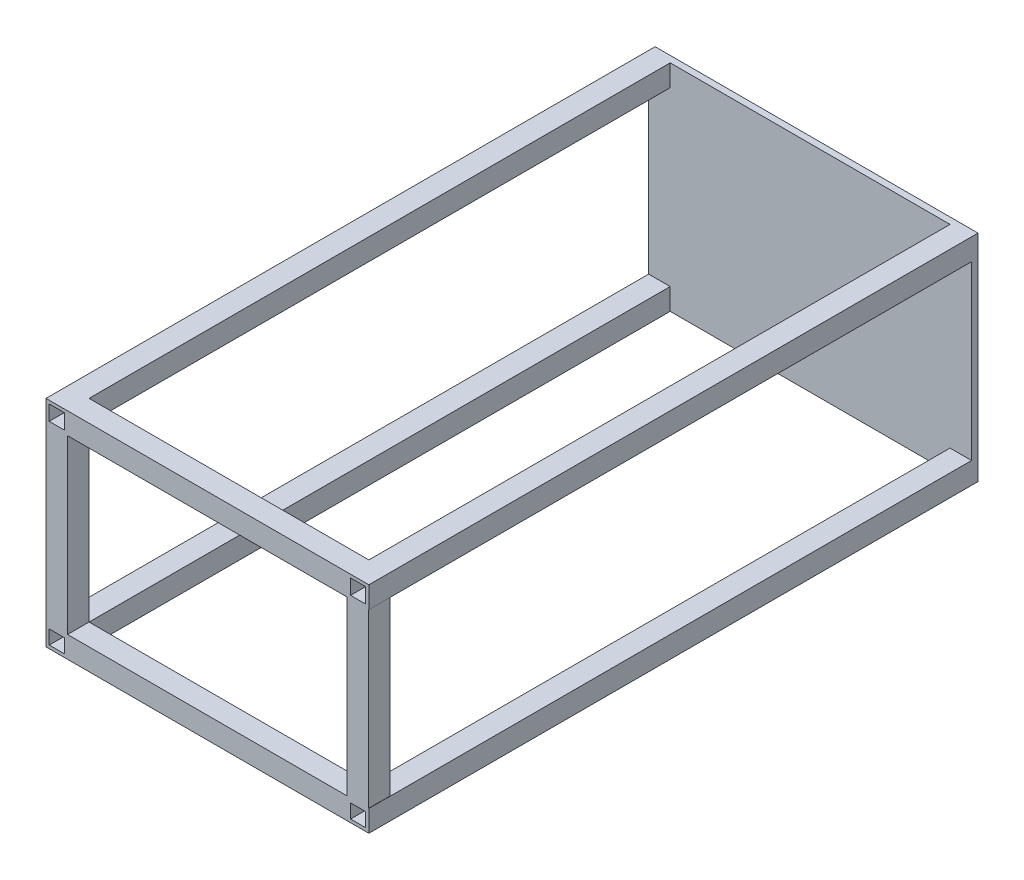
SolidWorks part; units mm, degrees
ref_plane "Front Plane" through (0, 0, 0) normal (0, 0, 1) x (1, 0, 0)
ref_plane "Top Plane" through (0, 0, 0) normal (0, 1, 0) x (1, 0, 0)
ref_plane "Right Plane" through (0, 0, 0) normal (1, 0, 0) x (0, 0, -1)
sketch "Sketch1" plane through (0, 0, 0) normal (0, 0, 1) x (1, 0, 0)
  line L1 (0, 0) -> (150, 0)
  line L2 (0, 0) -> (0, 100)
  line L3 (0, 100) -> (150, 100)
  line L4 (150, 0) -> (150, 100)
  dimension "D1" = 100
  dimension "D2" = 150
extrude "Boss-Extrude1" add sketch "Sketch1" along normal blind 3
sketch "Sketch2" plane through (0, 0, 3) normal (0, 0, 1) x (1, 0, 0)
  line L1 (150, 100) -> (140, 100)
  line L2 (150, 100) -> (150, 90)
  line L3 (150, 90) -> (140, 90)
  line L4 (140, 100) -> (140, 90)
  line L5 (150, 0) -> (140, 0)
  line L6 (150, 0) -> (150, 10)
  line L7 (150, 10) -> (140, 10)
  line L8 (140, 0) -> (140, 10)
  line L9 (0, 0) -> (10, 0)
  line L10 (0, 0) -> (0, 10)
  line L11 (0, 10) -> (10, 10)
  line L12 (10, 0) -> (10, 10)
  line L13 (0, 100) -> (10, 100)
  line L14 (0, 100) -> (0, 90)
  line L15 (0, 90) -> (10, 90)
  line L16 (10, 100) -> (10, 90)
  line L17 (141.5, 91.5) -> (148.5, 91.5)
  line L18 (141.5, 91.5) -> (141.5, 98.5)
  line L19 (141.5, 98.5) -> (148.5, 98.5)
  line L20 (148.5, 91.5) -> (148.5, 98.5)
  line L21 (141.5, 8.5) -> (148.5, 8.5)
  line L22 (141.5, 8.5) -> (141.5, 1.5)
  line L23 (141.5, 1.5) -> (148.5, 1.5)
  line L24 (148.5, 8.5) -> (148.5, 1.5)
  line L25 (1.5, 1.5) -> (8.5, 1.5)
  line L26 (1.5, 1.5) -> (1.5, 8.5)
  line L27 (1.5, 8.5) -> (8.5, 8.5)
  line L28 (8.5, 1.5) -> (8.5, 8.5)
  line L29 (1.5, 91.5) -> (8.5, 91.5)
  line L30 (1.5, 91.5) -> (1.5, 98.5)
  line L31 (1.5, 98.5) -> (8.5, 98.5)
  line L32 (8.5, 91.5) -> (8.5, 98.5)
  point P36 (10, 95)
  dimension "D1" = 10
  dimension "D2" = 10
  dimension "D3" = 10
  dimension "D4" = 10
  dimension "D5" = 10
  dimension "D6" = 10
  dimension "D7" = 10
  dimension "D8" = 10
  dimension "D9" = 1.5
  dimension "D10" = 1.5
  dimension "D11" = 1.5
  dimension "D12" = 1.5
  dimension "D13" = 1.5
  dimension "D14" = 1.5
  dimension "D15" = 1.5
  dimension "D16" = 1.5
  dimension "D17" = 1.5
  dimension "D18" = 1.5
  dimension "D19" = 1.5
  dimension "D20" = 1.5
  dimension "D21" = 1.5
  dimension "D22" = 1.5
  dimension "D23" = 1.5
  dimension "D24" = 1.5
extrude "Boss-Extrude2" add sketch "Sketch2" along normal blind 280
sketch "Sketch3" plane through (140, 0, 0) normal (-1, 0, 0) x (0, 0, 1)
  line L0 (283, 90) -> (3, 90) construction
  line L1 (283, 100) -> (273, 100)
  line L2 (283, 100) -> (283, 90)
  line L3 (283, 90) -> (273, 90)
  line L4 (273, 100) -> (273, 90)
  line L6 (274.5, 91.5) -> (281.5, 91.5)
  line L7 (274.5, 91.5) -> (274.5, 98.5)
  line L8 (274.5, 98.5) -> (281.5, 98.5)
  line L9 (281.5, 91.5) -> (281.5, 98.5)
  dimension "D1" = 10
  dimension "D2" = 1.5
  dimension "D3" = 1.5
  dimension "D4" = 1.5
  dimension "D5" = 1.5
extrude "Boss-Extrude3" add sketch "Sketch3" along normal blind 130
sketch "Sketch4" plane through (140, 0, 0) normal (-1, 0, 0) x (0, 0, 1)
  line L0 (283, 0) -> (0, 0) construction
  line L1 (283, 10) -> (273, 10)
  line L2 (283, 10) -> (283, 0)
  line L3 (283, 0) -> (273, 0)
  line L4 (273, 10) -> (273, 0)
  line L6 (274.5, 1.5) -> (281.5, 1.5)
  line L7 (274.5, 1.5) -> (274.5, 8.5)
  line L8 (274.5, 8.5) -> (281.5, 8.5)
  line L9 (281.5, 1.5) -> (281.5, 8.5)
  dimension "D1" = 10
  dimension "D2" = 1.5
  dimension "D3" = 1.5
  dimension "D4" = 1.5
  dimension "D5" = 1.5
  dimension "D6" = 1.5
extrude "Boss-Extrude4" add sketch "Sketch4" along normal blind 130
sketch "Sketch5" plane through (0, 90, 0) normal (0, -1, 0) x (1, 0, 0)
  line L1 (148.4, 274.5) -> (141.4, 274.5)
  line L2 (10, 273) -> (0, 273)
  line L3 (10, 273) -> (10, 283)
  line L4 (10, 283) -> (0, 283)
  line L5 (0, 273) -> (0, 283)
  line L6 (1.5, 281.5) -> (8.5, 281.5)
  line L7 (1.5, 281.5) -> (1.5, 274.5)
  line L8 (1.5, 274.5) -> (8.5, 274.5)
  line L9 (8.5, 281.5) -> (8.5, 274.5)
  line L10 (141.4, 281.5) -> (141.4, 274.5)
  line L11 (148.4, 281.5) -> (141.4, 281.5)
  line L12 (148.4, 281.5) -> (148.4, 274.5)
  line L13 (149.9, 273) -> (149.9, 283)
  line L14 (139.9, 273) -> (149.9, 273)
  line L15 (139.9, 273) -> (139.9, 283)
  line L16 (139.9, 283) -> (149.9, 283)
  line L17 (150, 283) -> (150, 0) construction
  dimension "D1" = 1.5
  dimension "D2" = 1.5
  dimension "D3" = 1.5
  dimension "D4" = 1.5
  dimension "D5" = 0.1
extrude "Boss-Extrude5" add sketch "Sketch5" along normal blind 82
